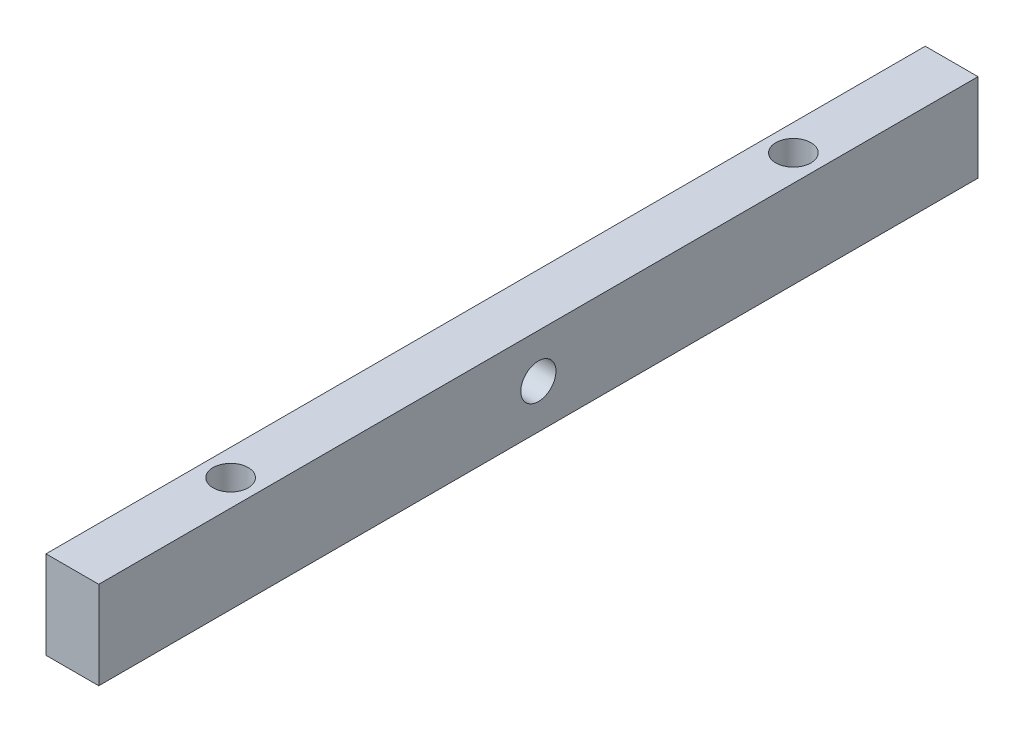
SolidWorks part; units mm, degrees
ref_plane "Спереди" through (0, 0, 0) normal (0, 0, 1) x (1, 0, 0)
ref_plane "Сверху" through (0, 0, 0) normal (0, 1, 0) x (1, 0, 0)
ref_plane "Справа" through (0, 0, 0) normal (1, 0, 0) x (0, 0, -1)
sketch "Эскиз1" plane through (0, 0, 0) normal (0, 0, 1) x (1, 0, 0)
  line L1 (-15, 25) -> (15, 25)
  line L2 (-15, 25) -> (-15, -25)
  line L3 (-15, -25) -> (15, -25)
  line L4 (15, 25) -> (15, -25)
  line L5 (-15, 25) -> (15, -25) construction
  line L6 (-15, -25) -> (15, 25) construction
  point P0 (0, 0)
  dimension "D2" = 30
extrude "Бобышка-Вытянуть1" add sketch "Эскиз1" along normal blind 500
sketch "Эскиз2" plane through (0, 25, 0) normal (0, 1, 0) x (1, 0, 0)
  line L0 (15, 0) -> (-15, 0) construction
  line L1 (-15, -250) -> (22.909, -250) construction
  line L2 (-15, -500) -> (-15, 0) construction
  circle A0 centre (0, -90) radius 10
  circle A1 centre (0, -410) radius 10
  dimension "D1" = 20
  dimension "D2" = 90
extrude "Вырез-Вытянуть1" cut sketch "Эскиз2" against normal through all
sketch "Эскиз3" plane through (-15, 0, 0) normal (-1, 0, 0) x (0, 0, 1)
  line L0 (250, 25) -> (250, -25) construction
  line L1 (500, 25) -> (0, 25) construction
  line L2 (500, -25) -> (0, -25) construction
  circle A0 centre (250, 0) radius 10
  dimension "D1" = 20
extrude "Вырез-Вытянуть2" cut sketch "Эскиз3" against normal through all
equation "\"h\"=50"
equation "\"D1@Эскиз1\"=\"h\""
equation "\"b1\"=30"
equation "\"D2@Эскиз1\"=\"b1\""
equation "\"x\"=500"
equation "\"D1@Бобышка-Вытянуть1\"=\"x\""
equation "\"k\"= 20"
equation "\"D1@Эскиз2\"=\"k\""
equation "\"p1\"=20"
equation "\"D1@Эскиз3\"=\"p1\""
